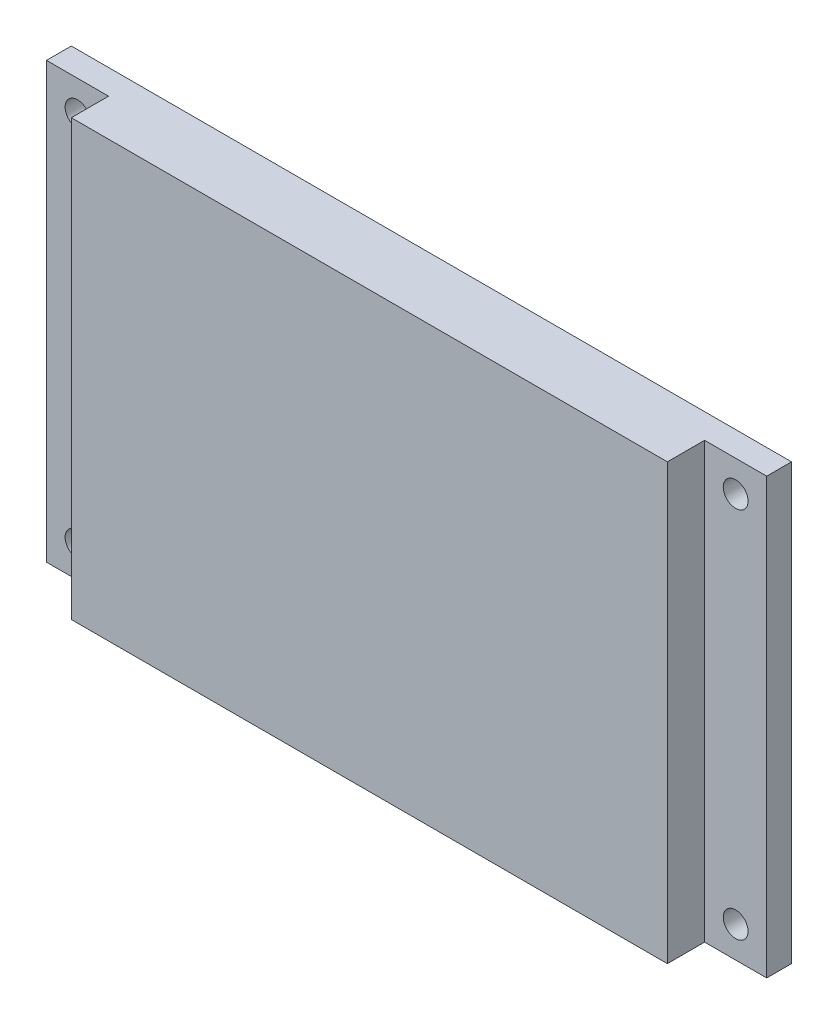
SolidWorks part; units mm, degrees
ref_plane "Front Plane" through (0, 0, 0) normal (0, 0, 1) x (1, 0, 0)
ref_plane "Top Plane" through (0, 0, 0) normal (0, 1, 0) x (1, 0, 0)
ref_plane "Right Plane" through (0, 0, 0) normal (1, 0, 0) x (0, 0, -1)
sketch "Sketch1" plane through (0, 0, 0) normal (0, 0, 1) x (1, 0, 0)
  line L1 (0, 0) -> (58, 0)
  line L2 (0, 0) -> (0, 35)
  line L3 (0, 35) -> (58, 35)
  line L4 (58, 0) -> (58, 35)
  line L5 (29, 35) -> (29, 0) construction
  line L6 (0, 17.5) -> (58, 17.5) construction
  circle A0 centre (2.5, 32.5) radius 1
  circle A1 centre (55.5, 32.5) radius 1
  circle A2 centre (2.5, 2.5) radius 1
  circle A3 centre (55.5, 2.5) radius 1
  point P148 (29, 17.5)
  dimension "D5" = 2
  dimension "D1" = 35
  dimension "D2" = 58
  dimension "D3" = 2.5
  dimension "D4" = 2.5
extrude "Boss-Extrude1" add sketch "Sketch1" along normal blind 2
sketch "Sketch2" plane through (0, 0, 2) normal (0, 0, 1) x (1, 0, 0)
  line L0 (58, 35) -> (0, 35) construction
  line L1 (5, 35) -> (53, 35)
  line L2 (5, 35) -> (5, 0)
  line L3 (5, 0) -> (53, 0)
  line L4 (53, 35) -> (53, 0)
  line L5 (29, 0) -> (29, 35) construction
  line L6 (5, 17.5) -> (53, 17.5) construction
  line L7 (0, 0) -> (58, 0) construction
  line L8 (0, 35) -> (0, 0) construction
  line L9 (58, 0) -> (58, 35) construction
  point P212 (29, 17.5)
  dimension "D1" = 5
  dimension "D2" = 5
extrude "Boss-Extrude2" add sketch "Sketch2" along normal blind 3
